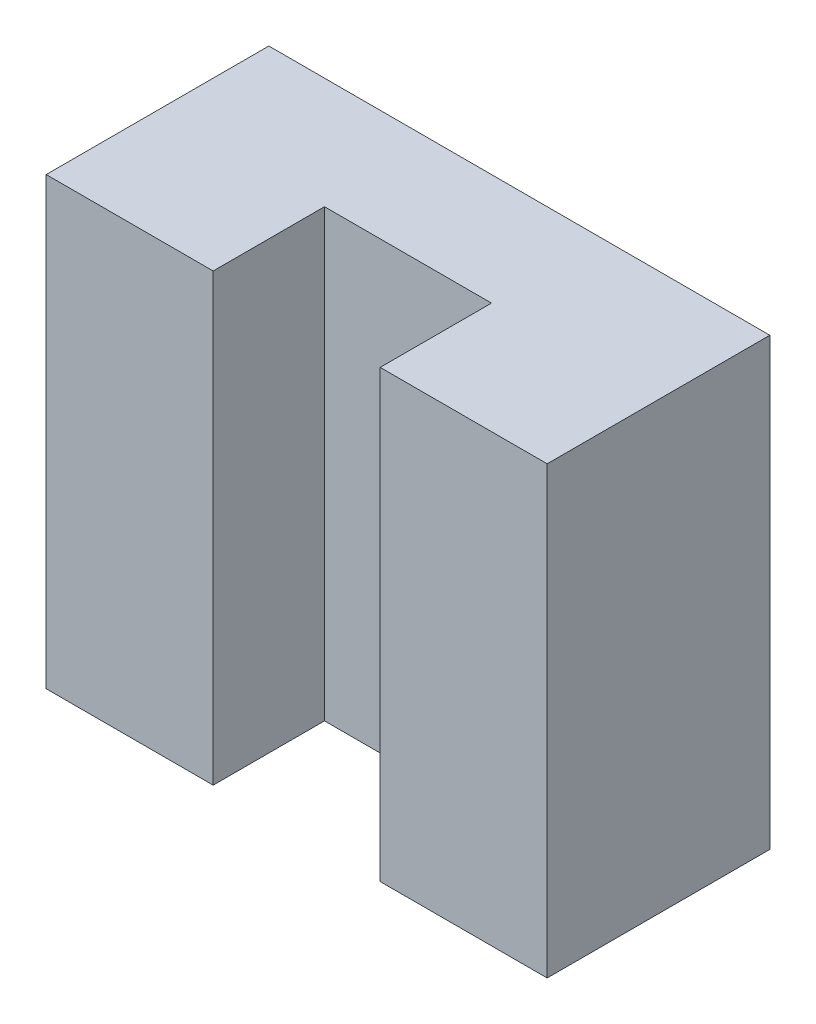
SolidWorks part; units mm, degrees
ref_plane "Front Plane" through (0, 0, 0) normal (0, 0, 1) x (1, 0, 0)
ref_plane "Top Plane" through (0, 0, 0) normal (0, 1, 0) x (1, 0, 0)
ref_plane "Right Plane" through (0, 0, 0) normal (1, 0, 0) x (0, 0, -1)
sketch "Sketch1" plane through (0, 0, 0) normal (0, 1, 0) x (1, 0, 0)
  line L0 (60, 0) -> (90, 0)
  line L1 (0, 0) -> (30, 0)
  line L2 (0, 0) -> (0, 40)
  line L3 (0, 40) -> (90, 40)
  line L4 (90, 0) -> (90, 40)
  line L6 (30, 0) -> (30, 20)
  line L7 (30, 20) -> (60, 20)
  line L8 (60, 0) -> (60, 20)
  point P4 (45, 0)
extrude "Boss-Extrude1" add sketch "Sketch1" along normal blind 80
